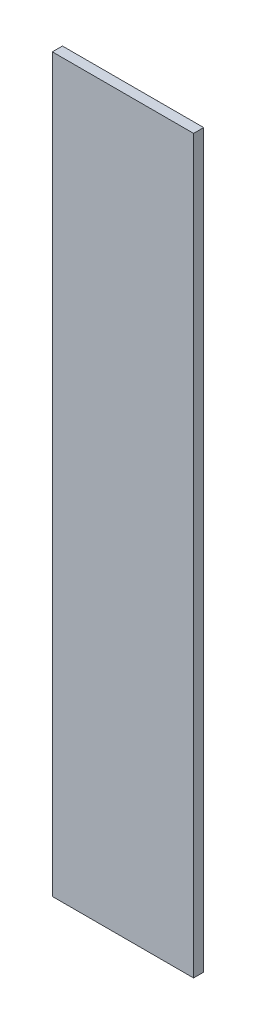
SolidWorks part; units mm, degrees
material "Oak"
ref_plane "Front Plane" through (0, 0, 0) normal (0, 0, 1) x (1, 0, 0)
ref_plane "Top Plane" through (0, 0, 0) normal (0, 1, 0) x (1, 0, 0)
ref_plane "Right Plane" through (0, 0, 0) normal (1, 0, 0) x (0, 0, -1)
sketch "Sketch1" plane through (0, 0, 0) normal (0, 0, 1) x (1, 0, 0)
  line L1 (-88.9, -460.375) -> (88.9, -460.375)
  line L2 (-88.9, -460.375) -> (-88.9, 460.375)
  line L3 (-88.9, 460.375) -> (88.9, 460.375)
  line L4 (88.9, -460.375) -> (88.9, 460.375)
  line L5 (-88.9, -460.375) -> (88.9, 460.375) construction
  line L6 (-88.9, 460.375) -> (88.9, -460.375) construction
  point P0 (0, 0)
  dimension "D1" = 920.75
  dimension "D2" = 177.8
extrude "Boss-Extrude1" add sketch "Sketch1" along normal blind 12.7
